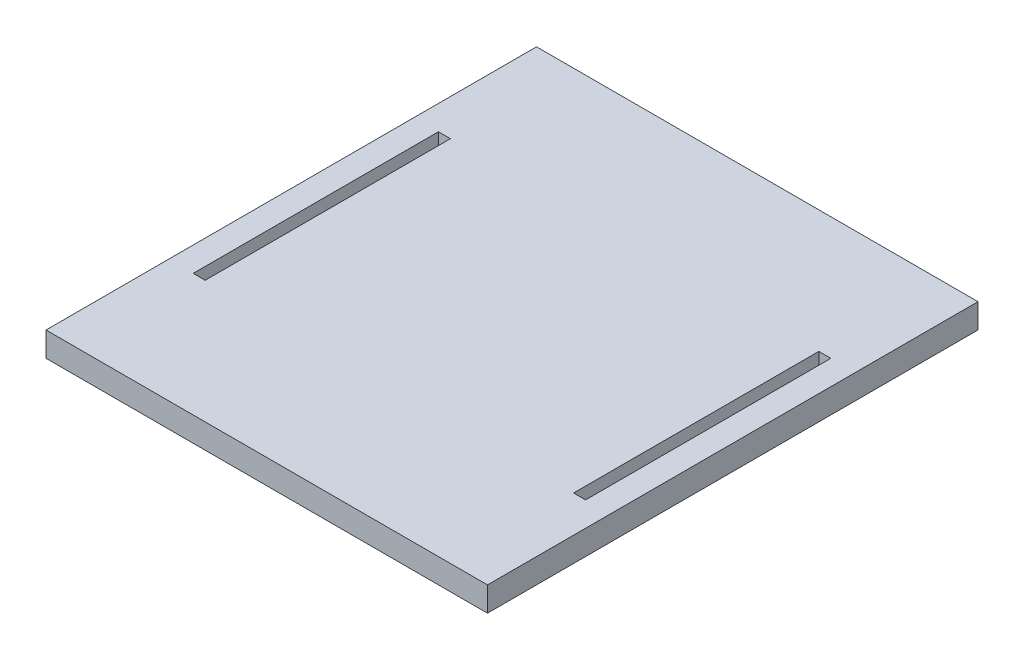
SolidWorks part; units mm, degrees
ref_plane "Alzado" through (0, 0, 0) normal (0, 0, 1) x (1, 0, 0)
ref_plane "Planta" through (0, 0, 0) normal (0, 1, 0) x (1, 0, 0)
ref_plane "Vista lateral" through (0, 0, 0) normal (1, 0, 0) x (0, 0, -1)
sketch "Croquis1" plane through (0, 0, 0) normal (0, 1, 0) x (1, 0, 0)
  line L0 (-90, 0) -> (90, 0) construction
  line L1 (-90, -100) -> (90, -100)
  line L2 (-90, -100) -> (-90, 100)
  line L3 (-90, 100) -> (90, 100)
  line L4 (90, -100) -> (90, 100)
  line L5 (-90, -100) -> (90, 100) construction
  line L6 (-90, 100) -> (90, -100) construction
  line L8 (-80, -50) -> (-75.1, -50)
  line L9 (-80, -50) -> (-80, 50)
  line L10 (-80, 50) -> (-75.1, 50)
  line L11 (-75.1, -50) -> (-75.1, 50)
  line L12 (-80, -50) -> (-75.1, 50) construction
  line L13 (-80, 50) -> (-75.1, -50) construction
  line L14 (75.1, -50) -> (80, -50)
  line L15 (75.1, -50) -> (75.1, 50)
  line L16 (75.1, 50) -> (80, 50)
  line L17 (80, -50) -> (80, 50)
  line L18 (75.1, -50) -> (80, 50) construction
  line L19 (75.1, 50) -> (80, -50) construction
  point P0 (0, 0)
  point P8 (-77.55, 0)
  point P13 (77.55, 0)
  dimension "D1" = 200
  dimension "D2" = 180
  dimension "D3" = 100
  dimension "D4" = 10
  dimension "D5" = 4.9
  dimension "D6" = 4.9
  dimension "D7" = 10
extrude "Saliente-Extruir1" add sketch "Croquis1" along normal blind 10
